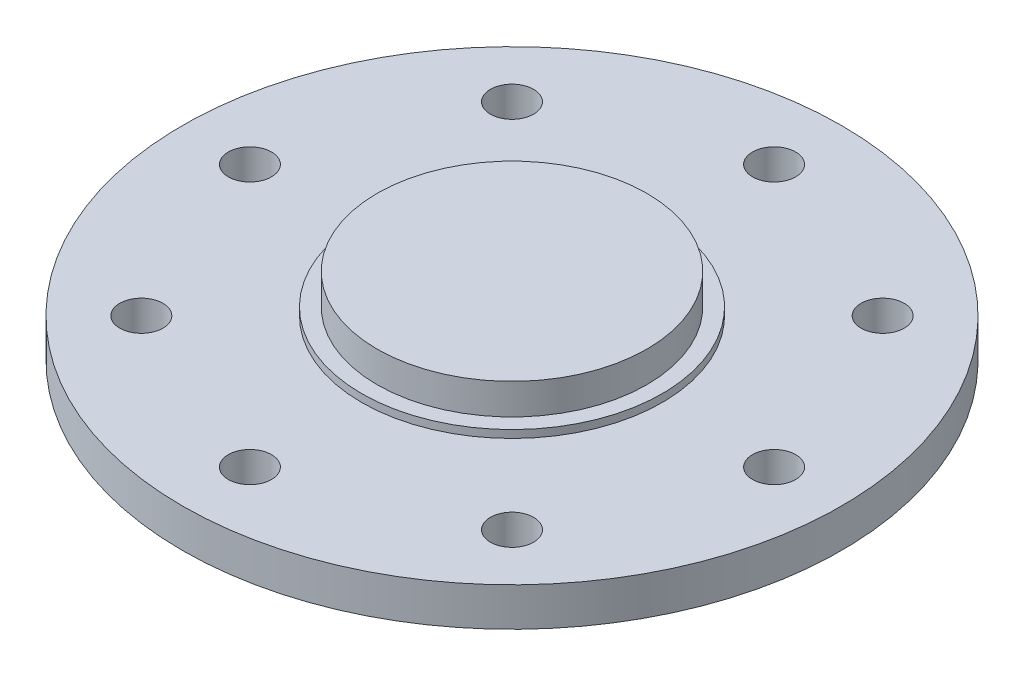
SolidWorks part; units mm, degrees
ref_plane "Front Plane" through (0, 0, 0) normal (0, 0, 1) x (1, 0, 0)
ref_plane "Top Plane" through (0, 0, 0) normal (0, 1, 0) x (1, 0, 0)
ref_plane "Right Plane" through (0, 0, 0) normal (1, 0, 0) x (0, 0, -1)
sketch "Sketch1" plane through (0, 0, 0) normal (0, 1, 0) x (1, 0, 0)
  circle A2 centre (0, 0) radius 42.75
  dimension "D1" = 85.5
extrude "Boss-Extrude1" add sketch "Sketch1" along normal blind 5
sketch "Sketch2" plane through (0, 5, 0) normal (0, 1, 0) x (1, 0, 0)
  circle A0 centre (0, 0) radius 34 construction
  circle A1 centre (0, 34) radius 2.8
  circle A2 centre (24.0416, 24.0416) radius 2.8
  circle A3 centre (34, 0) radius 2.8
  circle A4 centre (24.0416, -24.0416) radius 2.8
  circle A5 centre (0, -34) radius 2.8
  circle A6 centre (-24.0416, -24.0416) radius 2.8
  circle A7 centre (-34, 0) radius 2.8
  circle A8 centre (-24.0416, 24.0416) radius 2.8
  point P5 (-50.4935, 0)
  point P6 (0, 0)
  point P7 (0, 0)
  point P14 (0, 0)
  dimension "D1" = 68
  dimension "D2" = 5.6
  dimension "D3" = 8
extrude "Cut-Extrude1" cut sketch "Sketch2" against normal through all
sketch "Sketch3" plane through (0, 5, 0) normal (0, 1, 0) x (1, 0, 0)
  circle A0 centre (0, 0) radius 17.5
  dimension "D1" = 35
extrude "Boss-Extrude2" add sketch "Sketch3" along normal blind 5
sketch "Sketch4" plane through (0, 5, 0) normal (0, 1, 0) x (1, 0, 0)
  circle A0 centre (0, 0) radius 19.5
  dimension "D1" = 39
extrude "Boss-Extrude3" add sketch "Sketch4" along normal blind 1
equation "\"N_pin\"= 24"
equation "\"R_pin\"= 60"
equation "\"d_pin\"= 13"
equation "\"e\"= 1.5"
equation "\"t_disk\"= 5"
equation "\"N_outpin\"= 8"
equation "\"R_outpin\"= 34"
equation "\"d_outpin\"= 13"
equation "\"N_lobes\"= \"N_pin\" - 1"
equation "\"d_outhole\"= \"d_outpin\" + 2 * \"e\""
equation "\"ratio\"= \"N_lobes\""
equation "\"d_center\"= 24"
equation "\"a_hole1\"= 0 / \"N_lobes\""
equation "\"a_hole2\"= 360 / \"N_disk\" / \"N_lobes\""
equation "\"a_hole3\"= 720 / \"N_disk\" / \"N_lobes\""
equation "\"N_disk\"= 3"
equation "\"t_gap\"= 1"
equation "\"L_stack\"= \"N_disk\" * \"t_disk\" + (\"N_disk\" - 1) * \"t_gap\""
equation "\"d_pinshaft\"= 6"
equation "\"d_ecc\"= 15"
equation "\"d_outbrg\"= 47"
equation "\"w_outbrg\"= 7"
equation "\"d_outshaft\"= 35"
equation "\"w_brg\"= 5"
equation "\"c_run\"= 0.5"
equation "\"c_ax\"= \"t_gap\""
equation "\"D_pocket\"= 2 * \"R_pin\" + \"d_pin\" + 2 * \"c_run\""
equation "\"h_pocket\"= \"L_stack\" + 2 * \"c_ax\""
equation "\"t_floor\"= 8"
equation "\"d_insert\"= 5.6"
equation "\"N_bolt\"= 8"
equation "\"R_bolt\"= \"D_pocket\" / 2 + 2 + \"d_insert\" / 2"
equation "\"D_housing\"= 2 * (\"R_bolt\" + \"d_insert\" / 2 + 2.5)"
equation "\"D1@Sketch2\"=\"R_outpin\"*2"
equation "\"D3@Sketch2\"=\"N_outpin\""
equation "\"D1@Sketch3\"=\"d_outshaft\""
equation "\"D1@Sketch1\"=\"R_outpin\"*2+\"d_outshaft\"*0.5"
equation "\"D1@Sketch4\"=\"d_outshaft\"+2+2"
equation "\"D1@Boss-Extrude3\"=\"t_gap\""
